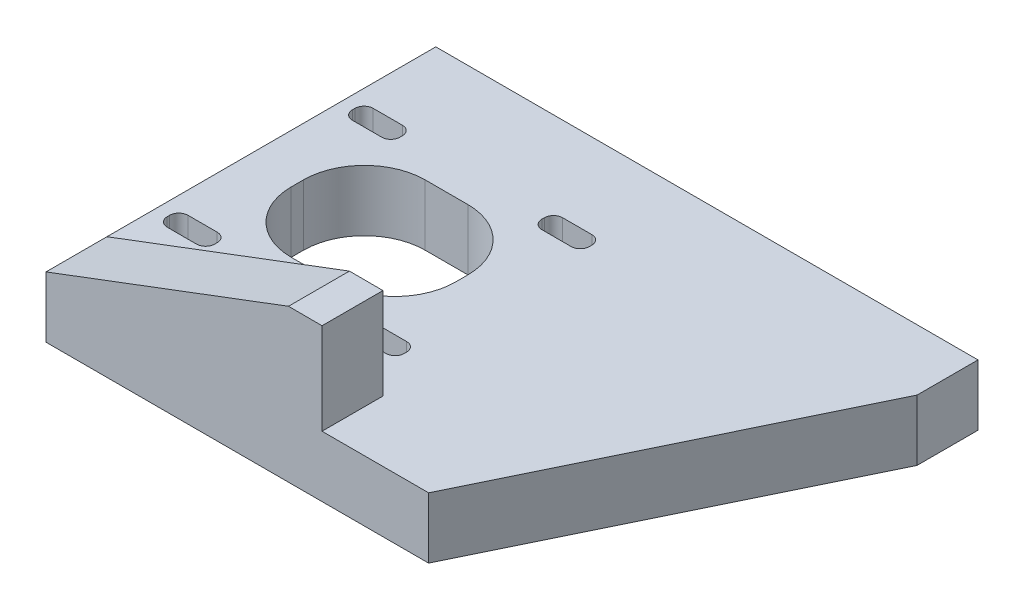
SolidWorks part; units mm, degrees
ref_plane "Спереди" through (0, 0, 0) normal (0, 0, 1) x (1, 0, 0)
ref_plane "Сверху" through (0, 0, 0) normal (0, 1, 0) x (1, 0, 0)
ref_plane "Справа" through (0, 0, 0) normal (1, 0, 0) x (0, 0, -1)
other "Configuration Table"
sketch "Эскиз2" plane through (0, 0, 0) normal (0, 1, 0) x (1, 0, 0)
  line L0 (44.5, 31.9907) -> (44.5, 21.9907) construction
  line L1 (-44.5, 31.9907) -> (44.5, 31.9907)
  line L2 (-44.5, 31.9907) -> (-44.5, -31.9907)
  line L3 (-44.5, -31.9907) -> (18.3084, -31.9907)
  line L4 (44.5, 31.9907) -> (44.5, 21.9907)
  line L5 (0, 31.9907) -> (0, -31.9907) construction
  line L6 (-44.5, -31.9907) -> (44.5, 31.9907) construction
  line L7 (44.5, 21.9907) -> (18.3084, -31.9907)
  point P0 (0, 0)
  dimension "D1" = 62.8084
  dimension "D2" = 89
  dimension "D3" = 10
  dimension "D4" = 60
extrude "Бобышка-Вытянуть1" add sketch "Эскиз2" along normal blind 10
sketch "Эскиз3" plane through (0, 0, 31.9907) normal (0, 0, 1) x (1, 0, 0)
  line L1 (-44.5, 0) -> (0.8056, 0)
  line L2 (-44.5, 0) -> (-44.5, 10)
  line L3 (-4.6944, 25.0172) -> (0.8056, 25)
  line L4 (0.8056, 0) -> (0.8056, 25)
  line L5 (0.8056, 25) -> (-4.6944, 25.0172) construction
  line L6 (-44.5, 0) -> (-44.5, 10) construction
  line L7 (-4.6944, 25.0172) -> (-44.5, 10)
  dimension "D1" = 25
  dimension "D2" = 10
  dimension "D4" = 5.5
extrude "Бобышка-Вытянуть2" add sketch "Эскиз3" against normal blind 10
sketch "Эскиз4" plane through (0, 10, 0) normal (0, 1, 0) x (1, 0, 0)
  line L0 (-38.5, -21.9907) -> (-38.5, -13.9907) construction
  line L1 (0.8056, -21.9907) -> (-44.5, -21.9907) construction
  line L2 (-38.5, -13.9907) -> (-44.5, -13.9907) construction
  line L3 (-44.5, 31.9907) -> (-44.5, -21.9907) construction
  line L4 (-38.5, -12.2907) -> (-38.5, 14.7093) construction
  line L5 (-40.9, -15.6907) -> (-36.1, -15.6907)
  line L6 (-42.4, -14.1907) -> (-42.4, -13.7907)
  line L7 (-40.9, -12.2907) -> (-36.1, -12.2907)
  line L8 (-34.6, -14.1907) -> (-34.6, -13.7907)
  line L9 (-42.4, -15.6907) -> (-34.6, -12.2907) construction
  line L10 (-42.4, -12.2907) -> (-34.6, -15.6907) construction
  line L11 (0, 1.2093) -> (-38.5, 1.2093) construction
  line L12 (-42.4, 14.7093) -> (-34.6, 18.1093) construction
  line L13 (0, 1.2093) -> (0, 0) construction
  line L14 (-42.4, 18.1093) -> (-34.6, 14.7093) construction
  line L15 (-38.5, 16.4093) -> (-44.5, 16.4093) construction
  line L16 (-38.5, 24.4093) -> (-38.5, 16.4093) construction
  line L17 (-34.6, 16.6093) -> (-34.6, 16.2093)
  line L18 (-40.9, 14.7093) -> (-36.1, 14.7093)
  line L19 (-42.4, 16.6093) -> (-42.4, 16.2093)
  line L20 (-40.9, 18.1093) -> (-36.1, 18.1093)
  line L21 (-34.6, 16.4093) -> (-11.3, 16.4093) construction
  line L22 (-22.95, 16.4093) -> (-22.95, 1.2093) construction
  line L23 (-3.5, -12.2907) -> (-11.3, -15.6907) construction
  line L24 (-3.5, -15.6907) -> (-11.3, -12.2907) construction
  line L25 (-7.4, -13.9907) -> (-1.4, -13.9907) construction
  line L26 (-7.4, -21.9907) -> (-7.4, -13.9907) construction
  line L27 (-11.3, -14.1907) -> (-11.3, -13.7907)
  line L28 (-5, -12.2907) -> (-9.8, -12.2907)
  line L29 (-3.5, -14.1907) -> (-3.5, -13.7907)
  line L30 (-5, -15.6907) -> (-9.8, -15.6907)
  line L31 (-11.3, 16.6093) -> (-11.3, 16.2093)
  line L32 (-7.4, 24.4093) -> (-7.4, 16.4093) construction
  line L33 (-5, 18.1093) -> (-9.8, 18.1093)
  line L34 (-3.5, 16.6093) -> (-3.5, 16.2093)
  line L35 (-5, 14.7093) -> (-9.8, 14.7093)
  arc A0 (-42.4, -13.7907) -> (-40.9, -12.2907) centre (-40.9, -13.7907) cw
  arc A1 (-40.9, -15.6907) -> (-42.4, -14.1907) centre (-40.9, -14.1907) cw
  arc A2 (-36.1, -15.6907) -> (-34.6, -14.1907) centre (-36.1, -14.1907) ccw
  arc A3 (-36.1, -12.2907) -> (-34.6, -13.7907) centre (-36.1, -13.7907) cw
  arc A4 (-36.1, 14.7093) -> (-34.6, 16.2093) centre (-36.1, 16.2093) ccw
  arc A5 (-36.1, 18.1093) -> (-34.6, 16.6093) centre (-36.1, 16.6093) cw
  arc A6 (-40.9, 18.1093) -> (-42.4, 16.6093) centre (-40.9, 16.6093) ccw
  arc A7 (-42.4, 16.2093) -> (-40.9, 14.7093) centre (-40.9, 16.2093) ccw
  arc A8 (-9.8, -12.2907) -> (-11.3, -13.7907) centre (-9.8, -13.7907) ccw
  arc A9 (-9.8, -15.6907) -> (-11.3, -14.1907) centre (-9.8, -14.1907) cw
  arc A10 (-5, -15.6907) -> (-3.5, -14.1907) centre (-5, -14.1907) ccw
  arc A11 (-3.5, -13.7907) -> (-5, -12.2907) centre (-5, -13.7907) ccw
  arc A12 (-9.8, 14.7093) -> (-11.3, 16.2093) centre (-9.8, 16.2093) cw
  arc A13 (-9.8, 18.1093) -> (-11.3, 16.6093) centre (-9.8, 16.6093) ccw
  arc A14 (-5, 18.1093) -> (-3.5, 16.6093) centre (-5, 16.6093) cw
  arc A15 (-3.5, 16.2093) -> (-5, 14.7093) centre (-5, 16.2093) cw
  dimension "D5" = 1.5
  dimension "D1" = 6
  dimension "D2" = 8
  dimension "D3" = 7.8
  dimension "D4" = 3.4
  dimension "D6" = 27
  dimension "D7" = 23.3
extrude "Вырез-Вытянуть1" cut sketch "Эскиз4" against normal through all
sketch "Эскиз5" plane through (0, 10, 0) normal (0, 1, 0) x (1, 0, 0)
  line L0 (-7.4, 14.7093) -> (-7.4, -12.2907) construction
  line L1 (-9.8, 14.7093) -> (-5, 14.7093) construction
  line L2 (-5, -12.2907) -> (-9.8, -12.2907) construction
  line L3 (-38.5, 14.7093) -> (-38.5, -12.2907) construction
  line L4 (-40.9, 14.7093) -> (-36.1, 14.7093) construction
  line L5 (-36.1, -12.2907) -> (-40.9, -12.2907) construction
  line L6 (-7.4, 1.2093) -> (-38.5, 1.2093) construction
  line L8 (-19.45, 12.2093) -> (-26.45, 12.2093)
  line L9 (-9.45, 2.2093) -> (-9.45, 0.2093)
  line L10 (-19.45, -9.7907) -> (-26.45, -9.7907)
  line L11 (-36.45, 2.2093) -> (-36.45, 0.2093)
  line L12 (-9.45, 12.2093) -> (-36.45, -9.7907) construction
  line L13 (-9.45, -9.7907) -> (-36.45, 12.2093) construction
  arc A0 (-26.45, -9.7907) -> (-36.45, 0.2093) centre (-26.45, 0.2093) cw
  arc A1 (-9.45, 0.2093) -> (-19.45, -9.7907) centre (-19.45, 0.2093) cw
  arc A2 (-26.45, 12.2093) -> (-36.45, 2.2093) centre (-26.45, 2.2093) ccw
  arc A3 (-19.45, 12.2093) -> (-9.45, 2.2093) centre (-19.45, 2.2093) cw
  point P14 (-22.95, 1.2093)
  dimension "D3" = 10
  dimension "D1" = 27
  dimension "D2" = 22
extrude "Вырез-Вытянуть2" cut sketch "Эскиз5" against normal through all
